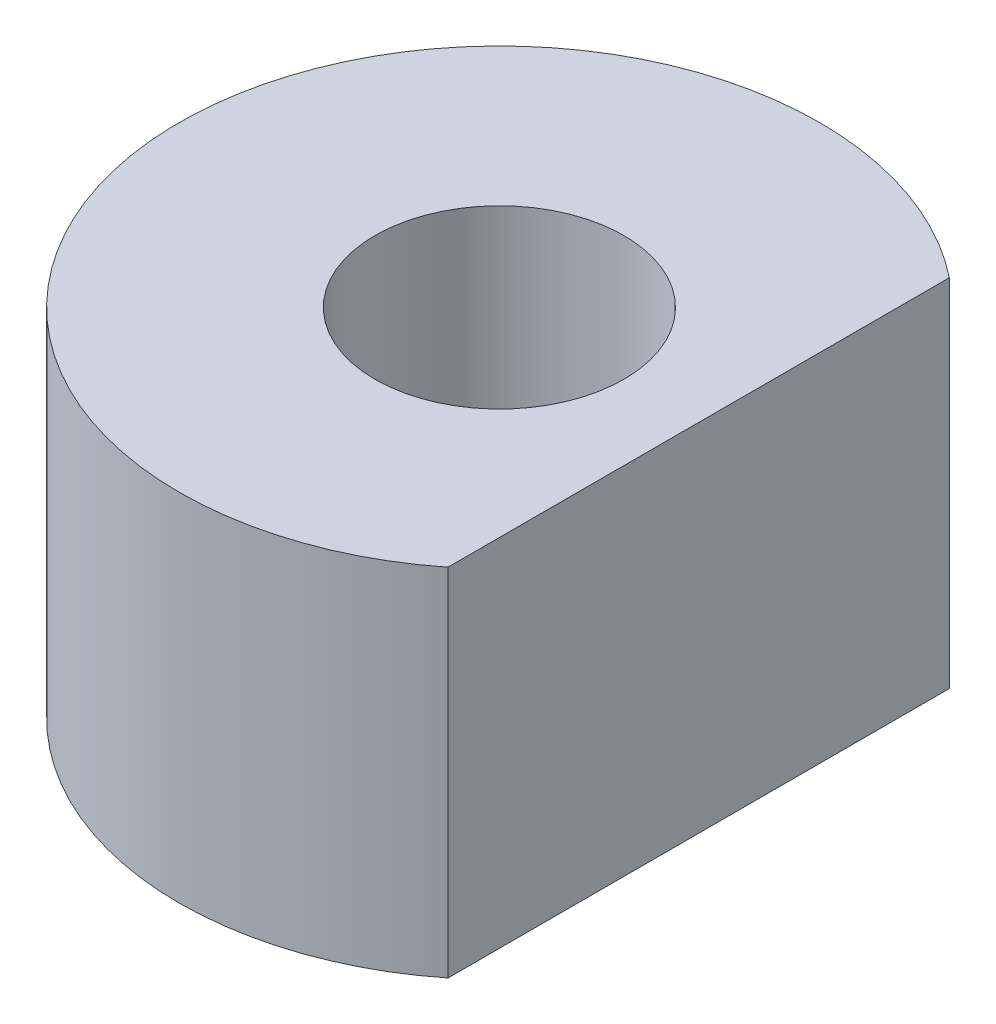
SolidWorks part; units mm, degrees
ref_plane "前视基准面" through (0, 0, 0) normal (0, 0, 1) x (1, 0, 0)
ref_plane "上视基准面" through (0, 0, 0) normal (0, 1, 0) x (1, 0, 0)
ref_plane "右视基准面" through (0, 0, 0) normal (1, 0, 0) x (0, 0, -1)
other "Configuration Table"
sketch "草图2" plane through (0, 0, 0) normal (0, 1, 0) x (1, 0, 0)
  line L0 (2.8, 3.5228) -> (2.8, -3.5228)
  circle A18 centre (0, 0) radius 4.5
  circle A19 centre (0, 0) radius 1.75
  dimension "D1" = 3.5
  dimension "D2" = 9
  dimension "D3" = 2.8
extrude "凸台-拉伸1" add sketch "草图2" along normal blind 5 contours L0 A18 A19
